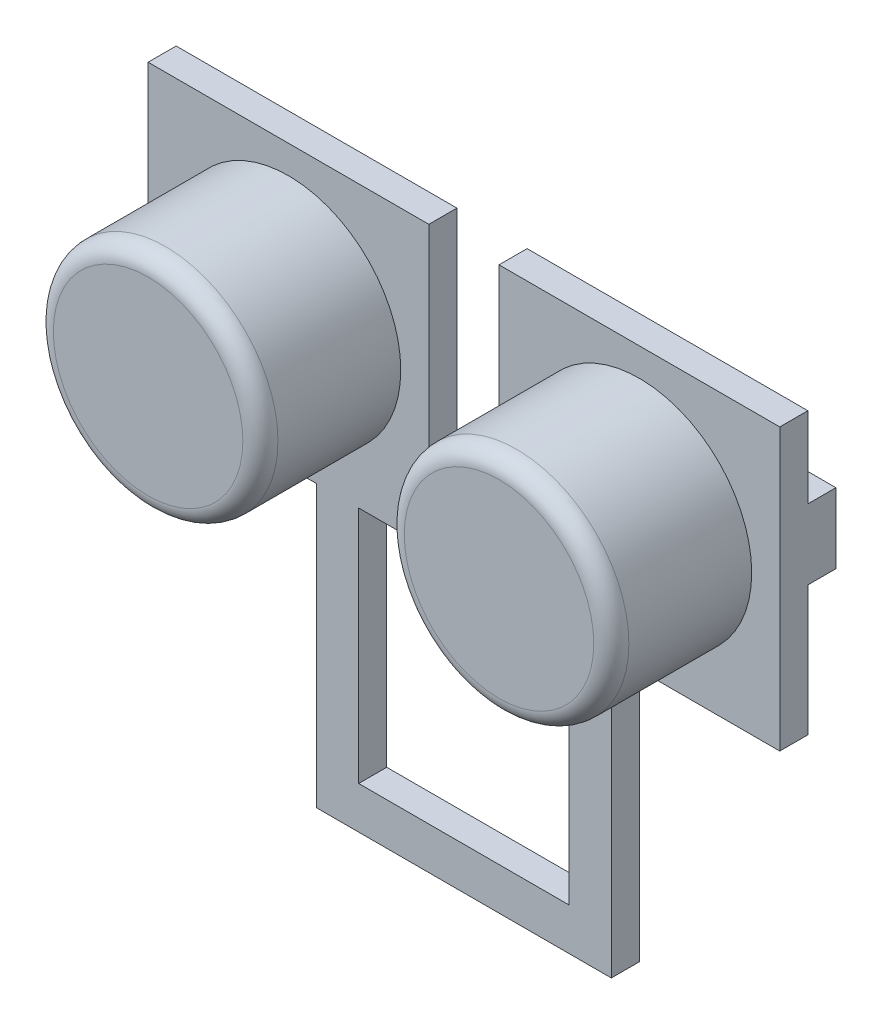
SolidWorks part; units mm, degrees
ref_plane "Спереди" through (0, 0, 0) normal (0, 0, 1) x (1, 0, 0)
ref_plane "Сверху" through (0, 0, 0) normal (0, 1, 0) x (1, 0, 0)
ref_plane "Справа" through (0, 0, 0) normal (1, 0, 0) x (0, 0, -1)
other "Configuration Table"
sketch "Эскиз1" plane through (0, 0, 0) normal (0, 0, 1) x (1, 0, 0)
  circle A0 centre (-8, 0.7) radius 0.8
  circle A1 centre (8, 0.7) radius 0.8
  circle A2 centre (-5, 0) radius 4
  circle A3 centre (5, 0) radius 4
sketch "Эскиз2" plane through (0, 0, 0) normal (0, 0, 1) x (1, 0, 0)
  circle A0 centre (-5, 0) radius 3.2
  circle A1 centre (5, 0) radius 3.2
  circle A2 centre (-5, 0) radius 4 construction
  circle A3 centre (5, 0) radius 4 construction
  dimension "D1" = 0.8
  dimension "D2" = 0.8
extrude "Бобышка-Вытянуть1" add sketch "Эскиз2" along normal blind 4
sketch "Эскиз3" plane through (0, 0, 0) normal (0, 0, -1) x (-1, 0, 0)
  line L1 (-9, 4) -> (-1, 4)
  line L2 (-9, 4) -> (-9, -4)
  line L3 (-9, -4) -> (-1, -4)
  line L4 (-1, 4) -> (-1, -4)
  line L5 (1, 4) -> (9, 4)
  line L6 (1, 4) -> (1, -4)
  line L7 (1, -4) -> (9, -4)
  line L8 (9, 4) -> (9, -4)
  circle A4 centre (-5, 0) radius 4 construction
  circle A5 centre (5, 0) radius 4 construction
extrude "Бобышка-Вытянуть2" add sketch "Эскиз3" along normal blind 0.8
sketch "Эскиз4" plane through (0, 0, -0.8) normal (0, 0, -1) x (-1, 0, 0)
  line L0 (-9, 4) -> (-9, -4) construction
  line L1 (-9, 1.7) -> (-7, 1.7)
  line L2 (-9, 1.7) -> (-9, -0.3)
  line L3 (-9, -0.3) -> (-7, -0.3)
  line L4 (-7, 1.7) -> (-7, -0.3)
  line L5 (9, -4) -> (9, 4) construction
  line L6 (9, 1.7) -> (7, 1.7)
  line L7 (9, 1.7) -> (9, -0.3)
  line L8 (9, -0.3) -> (7, -0.3)
  line L9 (7, 1.7) -> (7, -0.3)
  circle A0 centre (-8, 0.7) radius 0.8 construction
  circle A1 centre (8, 0.7) radius 0.8 construction
  dimension "D1" = 1
  dimension "D2" = 1
  dimension "D3" = 1
  dimension "D4" = 1
  dimension "D5" = 1
  dimension "D6" = 1
extrude "Бобышка-Вытянуть3" add sketch "Эскиз4" along normal blind 0.8
sketch "Эскиз5" plane through (0, 0, -0.8) normal (0, 0, -1) x (-1, 0, 0)
  line L0 (-9, -4) -> (-1, -4) construction
  line L1 (-3, -4) -> (-4.2, -4)
  line L2 (-3, -4) -> (-3, -12)
  line L3 (-3, -12) -> (-4.2, -12)
  line L4 (-4.2, -4) -> (-4.2, -12)
  line L5 (-1, -4) -> (-1, 4) construction
  line L6 (3, -4) -> (4.2, -4)
  line L7 (3, -4) -> (3, -12)
  line L8 (3, -12) -> (4.2, -12)
  line L9 (4.2, -4) -> (4.2, -12)
  line L10 (3, -12) -> (-3, -12)
  line L11 (3, -12) -> (3, -10.8)
  line L12 (3, -10.8) -> (-3, -10.8)
  line L13 (-3, -12) -> (-3, -10.8)
  line L14 (1, 4) -> (1, -4) construction
  line M12 (-9, -4) -> (-1, -4)
  dimension "D1" = 2
  dimension "D2" = 1.2
  dimension "D3" = 1.2
  dimension "D4" = 2
  dimension "D5" = 1.2
  dimension "D6" = 8
extrude "Бобышка-Вытянуть4" add sketch "Эскиз5" against normal blind 0.8 contours L4 L3 L2 M12 | L7 L12 L2 L10 | L9 L6 L7 L8
fillet "Скругление1" radius 0.5 2 edges at (8.2, 0, 4) (-1.8, 0, 4)
